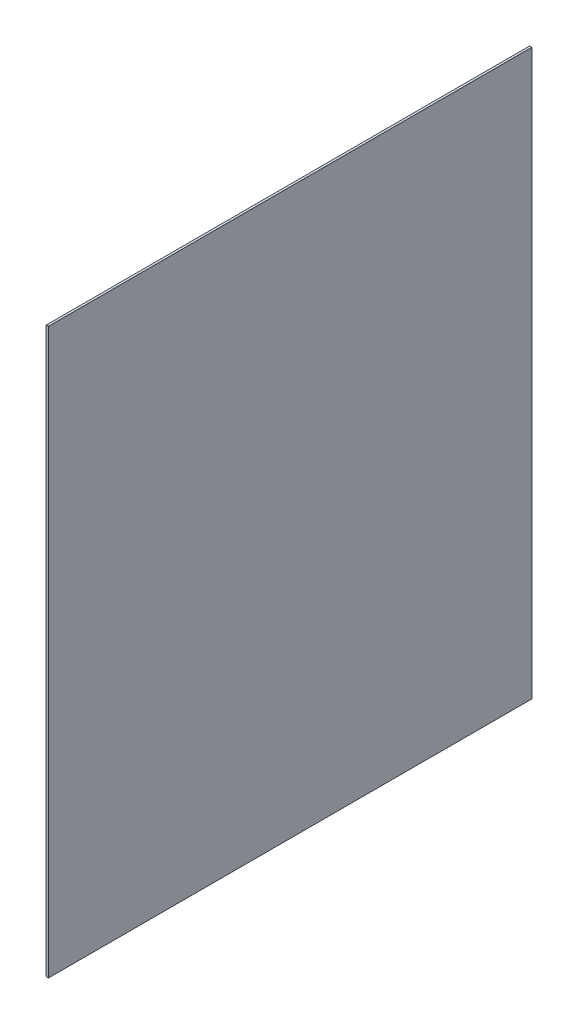
SolidWorks part; units mm, degrees
ref_plane "Front Plane" through (0, 0, 0) normal (0, 0, 1) x (1, 0, 0)
ref_plane "Top Plane" through (0, 0, 0) normal (0, 1, 0) x (1, 0, 0)
ref_plane "Right Plane" through (0, 0, 0) normal (1, 0, 0) x (0, 0, -1)
sketch3d "3DSketch1"
  line L4 (1335, 180.1075, -159.9951) -> (1335, 553.7618, -160.0082)
  line L5 (1335, 180.1075, 159.9951) -> (1335, 180.1075, -159.9951)
  line L6 (1335, 553.7618, 160.0082) -> (1335, 180.1075, 159.9951)
  line L7 (1335, 553.7618, -160.0082) -> (1335, 553.7618, 160.0082)
ref_plane "Plane1" through (1335, 0, 0) normal (1, 0, 0) x (0, 0, -1)
sketch "Sketch2" plane through (1335, 0, 0) normal (1, 0, 0) x (0, 0, -1)
  line L4 (159.9951, 180.1075) -> (160.0082, 553.7618)
  line L5 (160.0082, 553.7618) -> (-160.0082, 553.7618)
  line L6 (-160.0082, 553.7618) -> (-159.9951, 180.1075)
  line L7 (-159.9951, 180.1075) -> (159.9951, 180.1075)
  line L8 (159.9951, 180.1075) -> (160.0082, 553.7618)
  line L9 (160.0082, 553.7618) -> (-160.0082, 553.7618)
  line L10 (-160.0082, 553.7618) -> (-159.9951, 180.1075)
  line L11 (-159.9951, 180.1075) -> (159.9951, 180.1075)
  dimension "D1" = 0
extrude "Boss-Extrude2" add sketch "Sketch2" along normal blind 1.5 from offset 77.7
